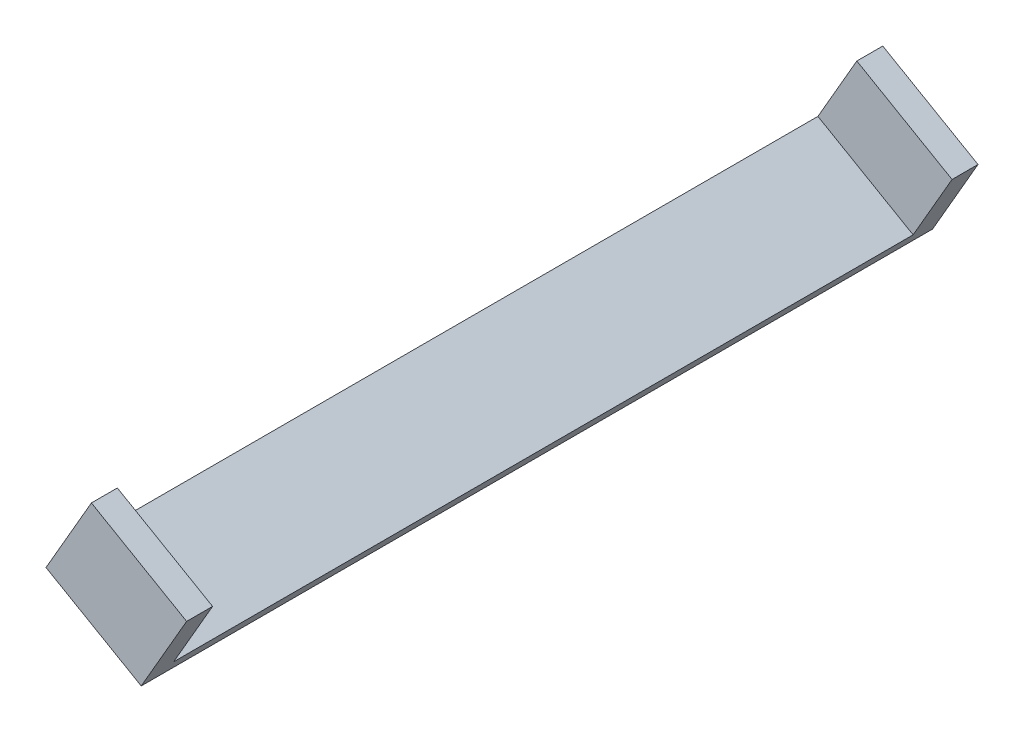
SolidWorks part; units mm, degrees
ref_plane "Front Plane" through (0, 0, 0) normal (0, 0, 1) x (1, 0, 0)
ref_plane "Top Plane" through (0, 0, 0) normal (0, 1, 0) x (1, 0, 0)
ref_plane "Right Plane" through (0, 0, 0) normal (1, 0, 0) x (0, 0, -1)
sketch "Sketch1" plane through (0, 0, 0) normal (0, 0, 1) x (1, 0, 0)
  line L0 (0, 0) -> (0, 146.8) construction
  line L1 (0, 0) -> (-146.8, 0) construction
  line L3 (0, 146.8) -> (10, 164.1205)
  line L4 (0, 146.8) -> (-146.8, 231.555)
  line L6 (-136.8, 248.8755) -> (10, 164.1205)
  line L7 (-146.8, 0) -> (-146.8, 231.555) construction
  line L8 (-146.8, 231.555) -> (-136.8, 248.8755)
  dimension "D1" = 146.8
  dimension "D2" = 146.8
  dimension "D3" = 20
extrude "Boss-Extrude1" add sketch "Sketch1" along normal blind 1220
sketch "Sketch4" plane through (73.5663, 127.4205, 0) normal (0.5, 0.866, 0) x (0.866, -0.5, 0)
  line L0 (-73.4, -1220) -> (-73.4, 0) construction
  line L1 (-242.91, -1220) -> (-73.4, -1220)
  line L2 (-242.91, -1220) -> (-242.91, -1180)
  line L3 (-242.91, -1180) -> (-73.4, -1180)
  line L4 (-73.4, -1220) -> (-73.4, -1180)
  line L5 (-242.91, -610) -> (592.0291, -610) construction
  line L6 (-242.91, -1220) -> (-242.91, 0) construction
  line L7 (-242.91, -40) -> (-73.4, -40)
  line L8 (-73.4, 0) -> (-73.4, -40)
  line L9 (-242.91, 0) -> (-73.4, 0)
  line L10 (-242.91, 0) -> (-242.91, -40)
  dimension "D1" = 40
extrude "Boss-Extrude3" add sketch "Sketch4" along normal blind 120
